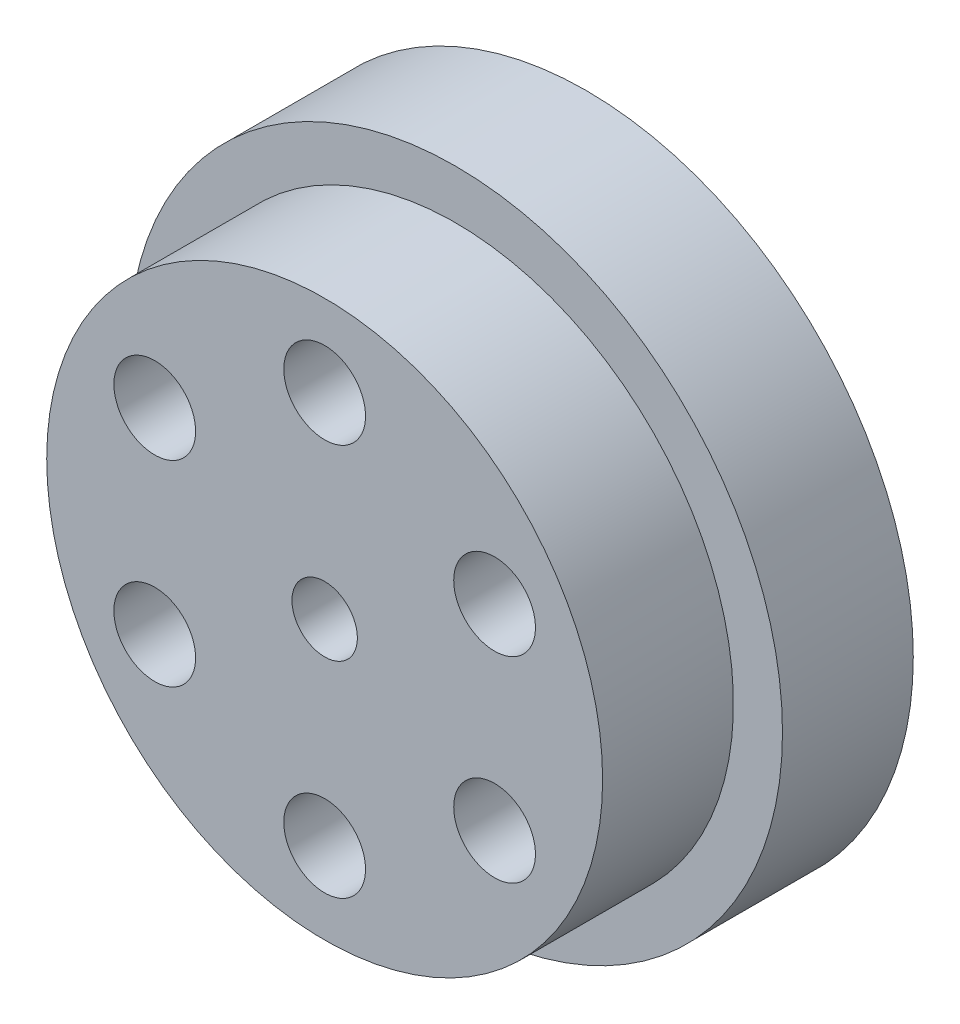
SolidWorks part; units mm, degrees
material "1060 合金"
ref_plane "前视基准面" through (0, 0, 0) normal (0, 0, 1) x (1, 0, 0)
ref_plane "上视基准面" through (0, 0, 0) normal (0, 1, 0) x (1, 0, 0)
ref_plane "右视基准面" through (0, 0, 0) normal (1, 0, 0) x (0, 0, -1)
other "Configuration Table"
sketch "草图1" plane through (0, 0, 0) normal (0, 0, 1) x (1, 0, 0)
  circle A0 centre (0, 0) radius 8.5
  circle A1 centre (0, 0) radius 2.5
  dimension "D1" = 17
  dimension "D2" = 5
extrude "凸台-拉伸1" add sketch "草图1" along normal blind 5
sketch "草图2" plane through (0, 0, 0) normal (0, 0, -1) x (-1, 0, 0)
  circle A0 centre (0, 0) radius 6 construction
  circle A1 centre (0, 6) radius 1.25
  circle A2 centre (5.1962, 3) radius 1.25
  circle A3 centre (5.1962, -3) radius 1.25
  circle A4 centre (0, -6) radius 1.25
  circle A5 centre (-5.1962, -3) radius 1.25
  circle A6 centre (-5.1962, 3) radius 1.25
  point P17 (0, 0)
  dimension "D1" = 12
  dimension "D2" = 2.5
  dimension "D3" = 6
extrude "切除-拉伸1" cut sketch "草图2" against normal blind 5
sketch "草图3" plane through (0, 0, 0) normal (0, 0, -1) x (-1, 0, 0)
  circle A0 centre (0, 0) radius 8.5
  circle A1 centre (0, 0) radius 10
  dimension "D1" = 17
  dimension "D2" = 20
extrude "凸台-拉伸2" add sketch "草图3" against normal blind 1
sketch "草图4" plane through (0, 0, 0) normal (0, 0, -1) x (-1, 0, 0)
  circle A0 centre (0, 0) radius 10
  circle A1 centre (0, 0) radius 2.5
  circle A2 centre (0, 6) radius 1.25
  circle A3 centre (5.1962, 3) radius 1.25
  circle A4 centre (5.1962, -3) radius 1.25
  circle A5 centre (0, -6) radius 1.25
  circle A6 centre (-5.1962, -3) radius 1.25
  circle A7 centre (-5.1962, 3) radius 1.25
  point P19 (0, 0)
  dimension "D2" = 5
  dimension "D3" = 2.5
  dimension "D4" = 20
  dimension "D1" = 6
extrude "凸台-拉伸3" add sketch "草图4" along normal blind 3
sketch "草图5" plane through (0, 0, 5) normal (0, 0, 1) x (1, 0, 0)
  circle A0 centre (0, 0) radius 2.5
  dimension "D1" = 5
extrude "凸台-拉伸4" add sketch "草图5" against normal blind 6
sketch "草图7" plane through (0, 0, -1) normal (0, 0, -1) x (-1, 0, 0)
  circle A0 centre (0, 0) radius 1
  dimension "D1" = 2
extrude "切除-拉伸2" cut sketch "草图7" against normal blind 10
